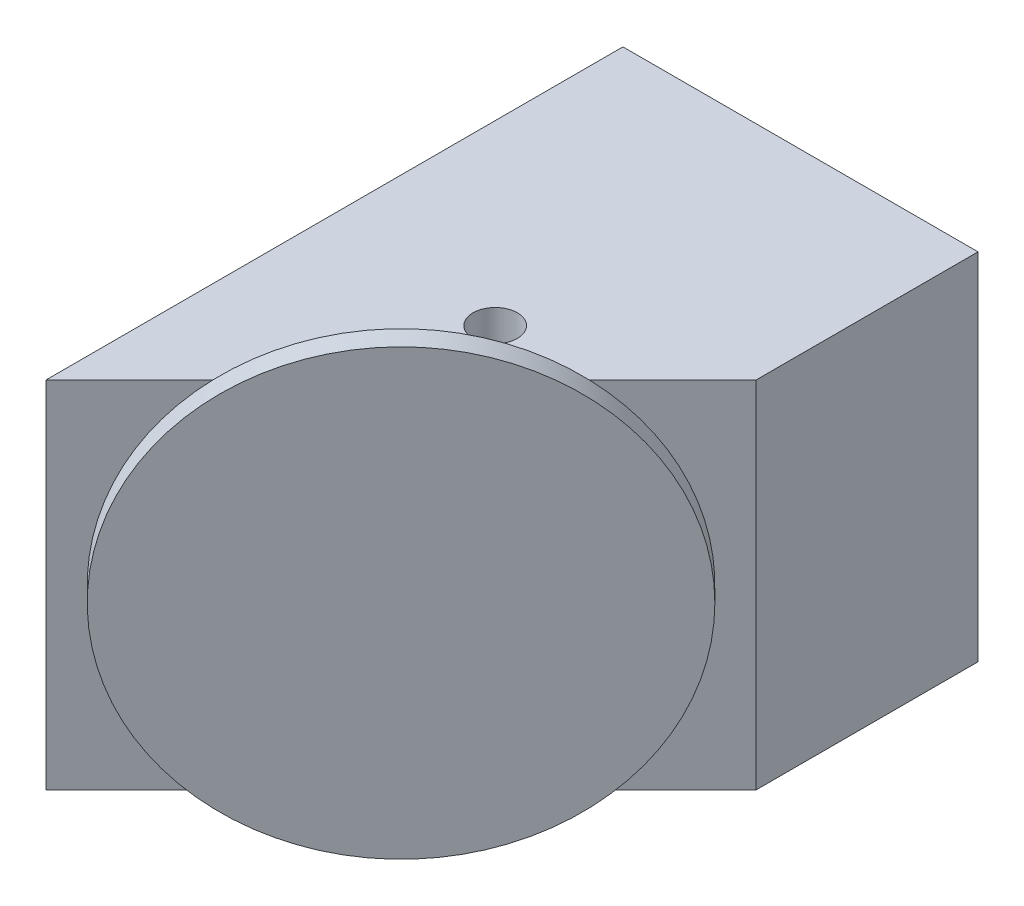
SolidWorks part; units mm, degrees
ref_plane "前视基准面" through (0, 0, 0) normal (0, 0, 1) x (1, 0, 0)
ref_plane "上视基准面" through (0, 0, 0) normal (0, 1, 0) x (1, 0, 0)
ref_plane "右视基准面" through (0, 0, 0) normal (1, 0, 0) x (0, 0, -1)
sketch "草图1" plane through (0, 0, 0) normal (0, 0, 1) x (1, 0, 0)
  line L1 (0, 0) -> (16, 0)
  line L2 (0, 0) -> (0, 16)
  line L3 (0, 16) -> (16, 16)
  line L4 (16, 0) -> (16, 16)
  line L5 (3, 3) -> (13, 3)
  line L6 (3, 3) -> (3, 13)
  line L7 (3, 13) -> (13, 13)
  line L8 (13, 3) -> (13, 13)
  point P5 (3, 3)
extrude "凸台-拉伸1" add sketch "草图1" along normal blind 10
sketch "草图2" plane through (0, 0, 0) normal (0, -1, 0) x (1, 0, 0)
  line L0 (0, 10) -> (0, 26)
  line L1 (0, 26) -> (16, 10)
  line L2 (16, 10) -> (0, 10)
sketch "草图5" plane through (0, 0, 0) normal (0, 0, -1) x (-1, 0, 0)
  line L1 (-3, 3) -> (-13, 3)
  line L2 (-3, 3) -> (-3, 13)
  line L3 (-3, 13) -> (-13, 13)
  line L4 (-13, 3) -> (-13, 13)
extrude "凸台-拉伸2" add sketch "草图2" against normal blind 16
sketch "草图6" plane through (13, 0, 13) normal (0.7071, 0, 0.7071) x (0.7071, 0, -0.7071)
  line L0 (-7.0711, 0) -> (-7.0711, 16)
  line L1 (4.2426, 0) -> (-18.3848, 0) construction
  line L2 (4.2426, 16) -> (-18.3848, 16) construction
  circle A0 centre (-7.0711, 8) radius 10
  point P8 (0, 0)
  point P9 (0, 0)
  line M1 (-18.3848, 0) -> (4.2426, 0)
  line M3 (4.2426, 16) -> (-18.3848, 16)
extrude "凸台-拉伸3" add sketch "草图6" along normal blind 1 contours A0 L0 M3 M1 | A0 M1 | A0 L0 M1 M3 | A0 M3
sketch "草图9" plane through (0, 0, 0) normal (0, -1, 0) x (-1, 0, 0)
  line L0 (-8, -18) -> (-5.8787, -15.8787)
  line L1 (-12.2426, -13.7574) -> (-3.7574, -22.2426) construction
  line L2 (-5.8787, -15.8787) -> (-16, -5.7574)
  line L3 (-16, -10) -> (-16, 0) construction
  line L4 (-8, 0) -> (-8, -13.7574)
  line L5 (0, 0) -> (-16, 0) construction
  circle A0 centre (-8, -13.7574) radius 1
extrude "切除-拉伸3" cut sketch "草图9" against normal blind 16 contours L2 A0 L4 | L2 A0 | L4 A0 L2
